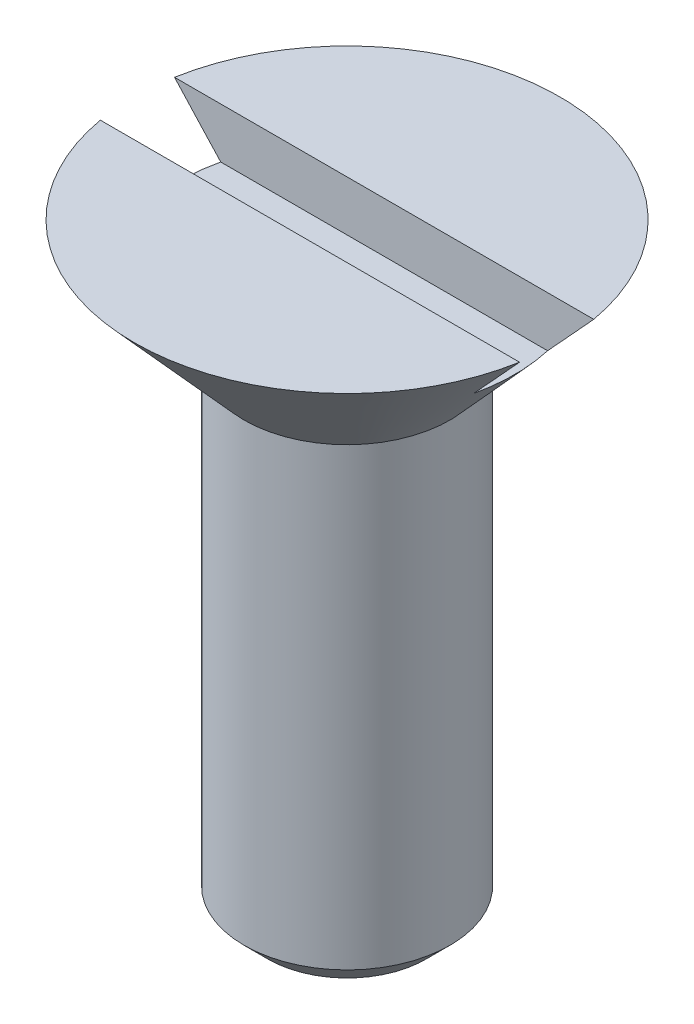
SolidWorks part; units mm, degrees
ref_plane "Front Plane" through (0, 0, 0) normal (0, 0, 1) x (1, 0, 0)
ref_plane "Top Plane" through (0, 0, 0) normal (0, 1, 0) x (1, 0, 0)
ref_plane "Right Plane" through (0, 0, 0) normal (1, 0, 0) x (0, 0, -1)
sketch "Sketch1" plane through (0, 0, 0) normal (0, 1, 0) x (1, 0, 0)
  circle A0 centre (0, 0) radius 1.0922
  dimension "D1" = 2.1844
extrude "Shaft" add sketch "Sketch1" against normal blind 5.08
sketch "Sketch3" plane through (0, 0, 0) normal (0, 0, 1) x (1, 0, 0)
  line L0 (0, 0) -> (0, 1.2954)
  line L1 (0, 1.2954) -> (2.2586, 1.2954)
  line L2 (1.0922, 0) -> (2.2586, 1.2954)
  line L3 (0, 0) -> (1.0922, 0)
  line L4 (0, 0) -> (0, 3.1168) construction
  dimension "D1" = 42
  dimension "D2" = 1.2954
revolve "Head" add sketch "Sketch3" angle 360 about L4
sketch "Sketch4" plane through (0, 1.2954, 0) normal (0, 1, 0) x (1, 0, 0)
  line L1 (-2.2586, -0.3937) -> (2.2586, -0.3937)
  line L2 (-2.2586, -0.3937) -> (-2.2586, 0.3937)
  line L3 (-2.2586, 0.3937) -> (2.2586, 0.3937)
  line L4 (2.2586, -0.3937) -> (2.2586, 0.3937)
  line L5 (-2.2586, -0.3937) -> (2.2586, 0.3937) construction
  line L6 (-2.2586, 0.3937) -> (2.2586, -0.3937) construction
  circle A0 centre (0, 0) radius 2.2586 construction
  point P0 (0, 0)
  dimension "D1" = 0.7874
extrude "Slot" cut sketch "Sketch4" against normal blind 0.5334
chamfer "Chamfer1" distance 0.254 angle 45 1 edges at (0, -5.08, 1.0922)
